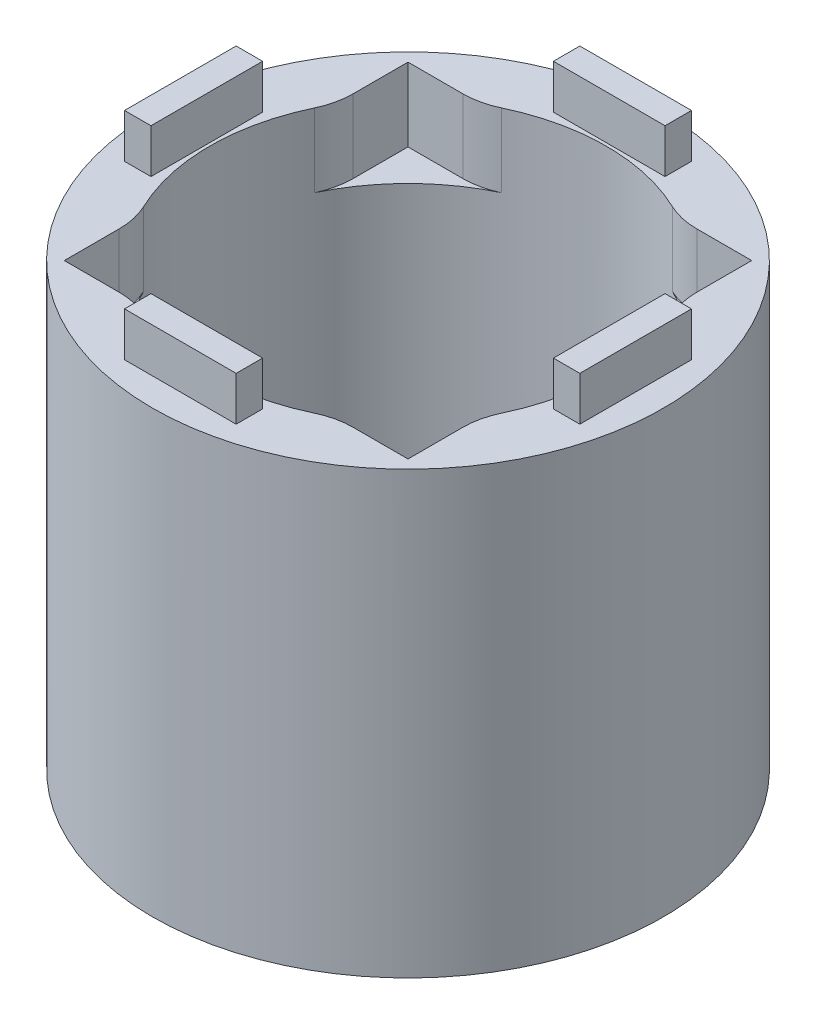
SolidWorks part; units mm, degrees
ref_plane "前视基准面" through (0, 0, 0) normal (0, 0, 1) x (1, 0, 0)
ref_plane "上视基准面" through (0, 0, 0) normal (0, 1, 0) x (1, 0, 0)
ref_plane "右视基准面" through (0, 0, 0) normal (1, 0, 0) x (0, 0, -1)
other "Configuration Table"
sketch "草图1" plane through (0, 0, 0) normal (0, 1, 0) x (1, 0, 0)
  circle A0 centre (0, 0) radius 17.4
  dimension "D1" = 34.8
extrude "凸台-拉伸1" add sketch "草图1" along normal blind 30
sketch "草图2" plane through (0, 30, 0) normal (0, 1, 0) x (1, 0, 0)
  line L1 (-13.5, 13.5) -> (13.5, 13.5)
  line L2 (-13.5, 13.5) -> (-13.5, -13.5)
  line L3 (-13.5, -13.5) -> (13.5, -13.5)
  line L4 (13.5, 13.5) -> (13.5, -13.5)
  line L5 (-13.5, 13.5) -> (13.5, -13.5) construction
  line L6 (-13.5, -13.5) -> (13.5, 13.5) construction
  line L9 (13.5, 4) -> (13.5, -4)
  circle A0 centre (0, 0) radius 13.5
  point P0 (0, 0)
  dimension "D1" = 27
  dimension "D2" = 27
extrude "切除-拉伸1" cut sketch "草图2" against normal through all contours A0 L4
sketch "草图3" plane through (0, 30, 0) normal (0, 1, 0) x (1, 0, 0)
  line L0 (0, 0) -> (15, 0)
  line L1 (3.8, -13.5) -> (-3.8, -13.5)
  line L2 (13.5, 3.8) -> (16.5, 3.8)
  line L3 (13.5, 3.8) -> (13.5, -3.8)
  line L4 (13.5, -3.8) -> (16.5, -3.8)
  line L5 (16.5, 3.8) -> (16.5, -3.8)
  line L6 (13.5, 3.8) -> (16.5, -3.8) construction
  line L7 (13.5, -3.8) -> (16.5, 3.8) construction
  line L8 (3.8, -13.5) -> (3.8, -16.5)
  line L9 (3.8, -16.5) -> (-3.8, -16.5)
  line L10 (-3.8, -13.5) -> (-3.8, -16.5)
  line L11 (-13.5, -3.8) -> (-13.5, 3.8)
  line L12 (-13.5, -3.8) -> (-16.5, -3.8)
  line L13 (-16.5, -3.8) -> (-16.5, 3.8)
  line L14 (-13.5, 3.8) -> (-16.5, 3.8)
  line L15 (-3.8, 13.5) -> (3.8, 13.5)
  line L16 (-3.8, 13.5) -> (-3.8, 16.5)
  line L17 (-3.8, 16.5) -> (3.8, 16.5)
  line L18 (3.8, 13.5) -> (3.8, 16.5)
  line L19 (15.5, 3.8) -> (15.5, -3.8)
  line L20 (3.8, -15.5) -> (-3.8, -15.5)
  line L21 (-15.5, -3.8) -> (-15.5, 3.8)
  line L22 (-3.8, 15.5) -> (3.8, 15.5)
  line L23 (13.7, 3.8) -> (13.7, -3.8)
  line L24 (3.8, -13.7) -> (-3.8, -13.7)
  line L25 (-13.7, -3.8) -> (-13.7, 3.8)
  line L26 (-3.8, 13.7) -> (3.8, 13.7)
  point P22 (0, 0)
  point P31 (0, 0)
  point P39 (0, 0)
  dimension "D1" = 15
  dimension "D2" = 3
  dimension "D3" = 7.6
  dimension "D5" = 1
  dimension "D6" = 4
  dimension "D7" = 0.2
  dimension "D8" = 4
  dimension "D4" = 4
extrude "凸台-拉伸2" add sketch "草图3" along normal blind 3
sketch "草图4" plane through (0, 0, 0) normal (1, 0, 0) x (0, 0, -1)
  line L0 (0, 0) -> (0, 5)
  line L2 (-10, 10) -> (10, 10)
  line L3 (-10, 10) -> (-10, 0)
  line L4 (-10, 0) -> (10, 0)
  line L5 (10, 10) -> (10, 0)
  line L6 (-10, 10) -> (10, 0) construction
  line L7 (-10, 0) -> (10, 10) construction
  dimension "D1" = 5
  dimension "D2" = 20
extrude "切除-拉伸2" cut sketch "草图4" against normal through all
fillet "圆角1" radius 5 2 edges at (-11.6543, 10, 10) (-11.6543, 10, -10)
sketch "草图5" plane through (0, 30, 0) normal (0, 1, 0) x (1, 0, 0)
  line L1 (-11.7, 11.7) -> (11.7, 11.7)
  line L2 (-11.7, 11.7) -> (-11.7, -11.7)
  line L3 (-11.7, -11.7) -> (11.7, -11.7)
  line L4 (11.7, 11.7) -> (11.7, -11.7)
  line L5 (-11.7, 11.7) -> (11.7, -11.7) construction
  line L6 (-11.7, -11.7) -> (11.7, 11.7) construction
  point P0 (0, 0)
  dimension "D1" = 23.4
  dimension "D2" = 23.4
extrude "切除-拉伸3" cut sketch "草图5" against normal blind 5
fillet "圆角2" radius 5 8 edges at (-6.735, 27.5, 11.7) (6.735, 27.5, 11.7) (-11.7, 27.5, -6.735) (-11.7, 27.5, 6.735) (11.7, 27.5, 6.735) (11.7, 27.5, -6.735) (6.735, 27.5, -11.7) (-6.735, 27.5, -11.7)
